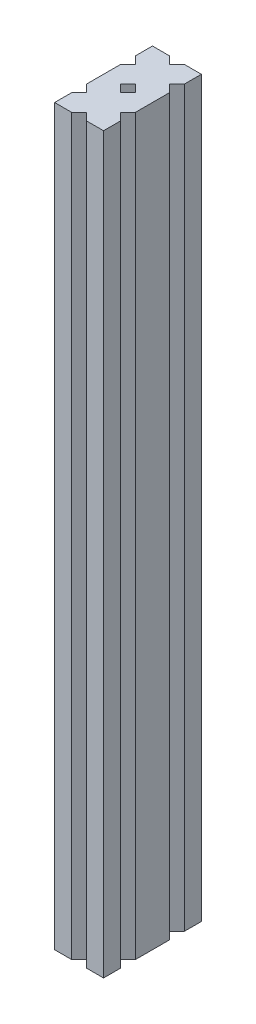
SolidWorks part; units mm, degrees
ref_plane "Front" through (0, 0, 0) normal (0, 0, 1) x (1, 0, 0)
ref_plane "Top" through (0, 0, 0) normal (0, 1, 0) x (1, 0, 0)
ref_plane "Right" through (0, 0, 0) normal (1, 0, 0) x (0, 0, -1)
sketch "Skizze1" plane through (0, 0, 0) normal (0, 1, 0) x (1, 0, 0)
  line L0 (0, 0) -> (0, 40)
  line L1 (0, 40) -> (20, 40)
  line L2 (20, 40) -> (20, 0)
  line L3 (20, 0) -> (0, 0)
  dimension "D1" = 20
  dimension "D2" = 40
extrude "Aufsatz-Linear austragen1" add sketch "Skizze1" along normal blind 300
sketch "Skizze2" plane through (0, 300, 0) normal (0, 1, 0) x (1, 0, 0)
  line L0 (10, 40) -> (10, 20) construction
  line L1 (0, 30) -> (20, 30) construction
  line L2 (7, 40) -> (10, 37)
  line L3 (13, 40) -> (10, 37)
  line L4 (10, 30) -> (20, 40) construction
  line L5 (7, 40) -> (13, 40)
  line L6 (20, 33) -> (17, 30)
  line L7 (20, 27) -> (17, 30)
  line L8 (20, 27) -> (20, 33)
  line L9 (0, 27) -> (0, 33)
  line L10 (0, 27) -> (3, 30)
  line L11 (0, 33) -> (3, 30)
  line L12 (7, 20) -> (13, 20)
  line L13 (13, 20) -> (10, 23)
  line L14 (7, 20) -> (10, 23)
  line L15 (0, 20) -> (20, 20) construction
  line L16 (0, 40) -> (0, 0) construction
  line L17 (20, 0) -> (20, 40) construction
  line L18 (20, 40) -> (0, 40) construction
  line L19 (7, 20) -> (10, 17)
  line L20 (13, 20) -> (10, 17)
  line L21 (20, 13) -> (17, 10)
  line L22 (20, 7) -> (17, 10)
  line L23 (20, 13) -> (20, 7)
  line L24 (13, 0) -> (10, 3)
  line L25 (7, 0) -> (13, 0)
  line L26 (7, 0) -> (10, 3)
  line L27 (0, 13) -> (3, 10)
  line L28 (0, 13) -> (0, 7)
  line L29 (0, 7) -> (3, 10)
  line M14 (0, 0) -> (20, 0)
  line M15 (20, 0) -> (20, 40)
  line M16 (20, 40) -> (0, 40)
  line M17 (0, 40) -> (0, 0)
  dimension "D1" = 3
  dimension "D2" = 3
extrude "Schnitt-Linear austragen1" cut sketch "Skizze2" against normal through all contours L11 L10 M17 | L3 L2 M16 | L7 L6 M15 | L20 L12 L19 | L14 L12 L13 | L22 L21 M15 | L29 L27 M17 | L26 L24 M14
